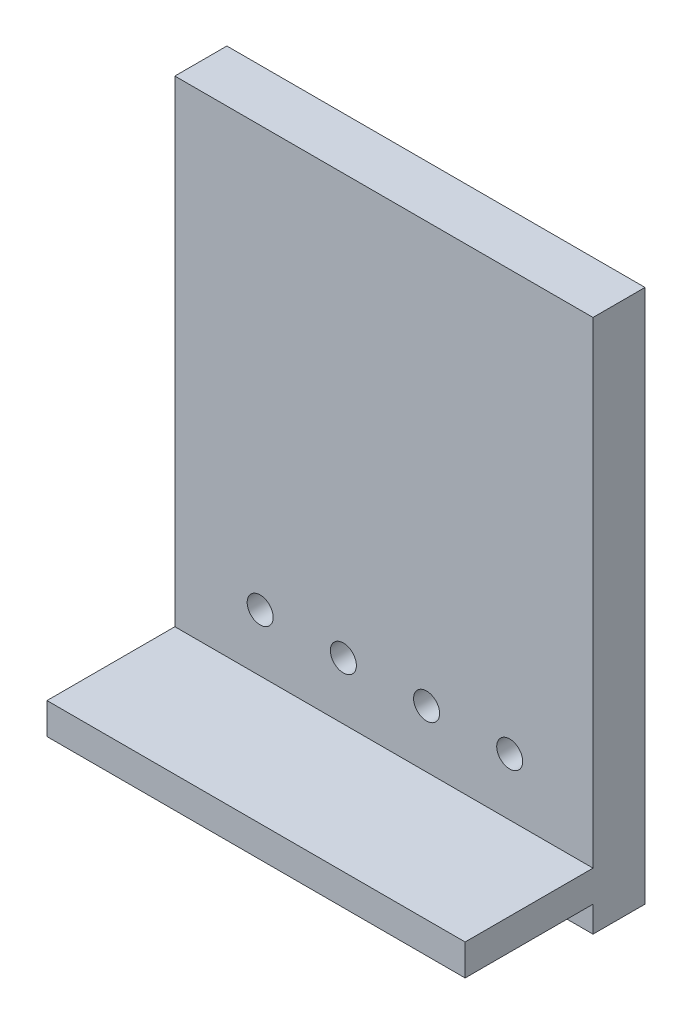
SolidWorks part; units mm, degrees
ref_plane "Front Plane" through (0, 0, 0) normal (0, 0, 1) x (1, 0, 0)
ref_plane "Top Plane" through (0, 0, 0) normal (0, 1, 0) x (1, 0, 0)
ref_plane "Right Plane" through (0, 0, 0) normal (1, 0, 0) x (0, 0, -1)
sketch "Sketch1" plane through (0, 0, 0) normal (0, 0, 1) x (1, 0, 0)
  line L1 (-53.4569, -1235.6805) -> (-13.2569, -1235.6805)
  line L2 (-53.4569, -1235.6805) -> (-53.4569, -1287.0305)
  line L3 (-53.4569, -1287.0305) -> (-13.2569, -1287.0305)
  line L4 (-13.2569, -1235.6805) -> (-13.2569, -1287.0305)
extrude "Boss-Extrude1" add sketch "Sketch1" along normal blind 5 contours L1 L4 L3 L2
sketch "Sketch2" plane through (0, 0, 5) normal (0, 0, 1) x (1, 0, 0)
  line L0 (-53.4569, -1287.0305) -> (-53.4569, -1279.0305) construction
  line L1 (-53.4569, -1235.6805) -> (-53.4569, -1287.0305) construction
  line L2 (-53.4569, -1279.0305) -> (-53.4569, -1283.0305) construction
  line L3 (-53.4569, -1283.0305) -> (-13.2569, -1283.0305) construction
  line L4 (-13.2569, -1235.6805) -> (-13.2569, -1287.0305) construction
  line L5 (-53.4569, -1283.0305) -> (-53.4569, -1281.5305)
  line L6 (-53.4569, -1281.5305) -> (-53.4569, -1284.5305)
  line L7 (-53.4569, -1284.5305) -> (-13.2569, -1284.5305)
  line L8 (-13.2569, -1284.5305) -> (-13.2569, -1281.5305)
  line L9 (-13.2569, -1281.5305) -> (-53.4569, -1281.5305)
  line M1 (-53.4569, -1235.6805) -> (-53.4569, -1287.0305)
  line M3 (-13.2569, -1287.0305) -> (-13.2569, -1235.6805)
extrude "Boss-Extrude2" add sketch "Sketch2" along normal blind 12.295 contours L9 L7 M3 M1
sketch "Sketch4" plane through (0, 0, 5) normal (0, 0, 1) x (1, 0, 0)
  circle A0 centre (-45.2569, -1276.0305) radius 1.25
  circle A1 centre (-37.2569, -1276.0305) radius 1.25
  circle A2 centre (-29.2569, -1276.0305) radius 1.25
  circle A3 centre (-21.2649, -1276.0305) radius 1.25
extrude "Cut-Extrude1" cut sketch "Sketch4" against normal blind 10
